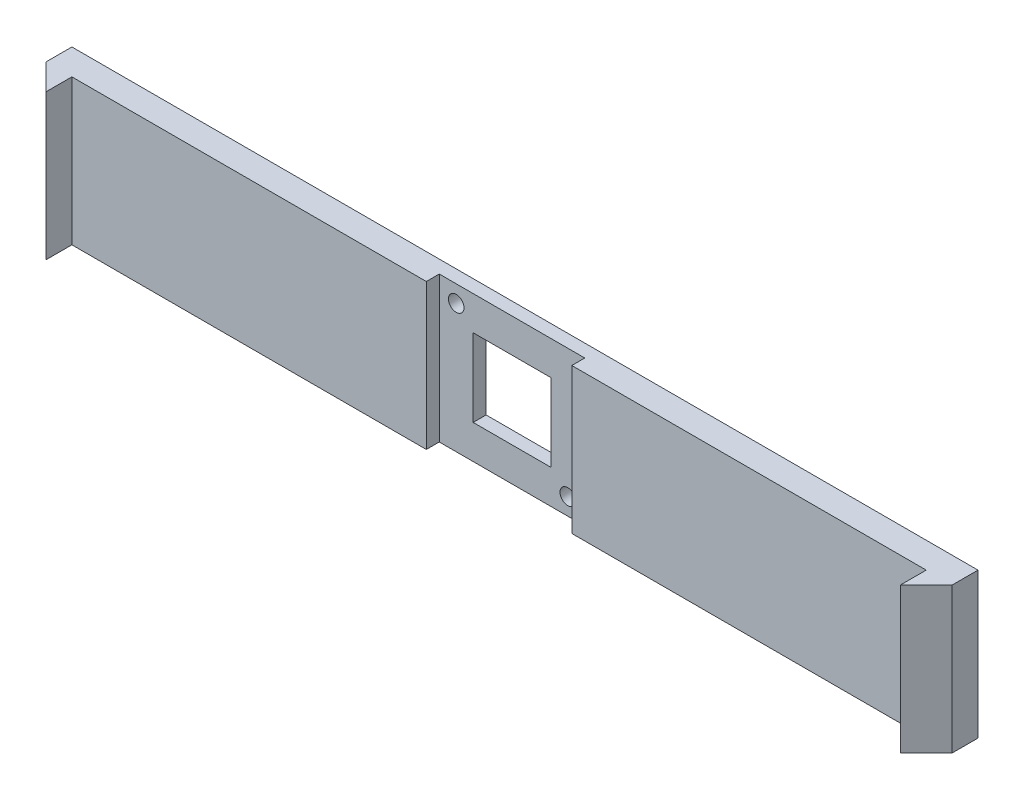
SolidWorks part; units mm, degrees
ref_plane "Front Plane" through (0, 0, 0) normal (0, 0, 1) x (1, 0, 0)
ref_plane "Top Plane" through (0, 0, 0) normal (0, 1, 0) x (1, 0, 0)
ref_plane "Right Plane" through (0, 0, 0) normal (1, 0, 0) x (0, 0, -1)
sketch "Sketch1" plane through (0, 0, 0) normal (0, 0, 1) x (1, 0, 0)
  line L1 (-165, -28.1) -> (165, -28.1)
  line L2 (-165, -28.1) -> (-165, 28.1)
  line L3 (-165, 28.1) -> (165, 28.1)
  line L4 (165, -28.1) -> (165, 28.1)
  line L5 (-165, -28.1) -> (165, 28.1) construction
  line L6 (-165, 28.1) -> (165, -28.1) construction
  point P0 (0, 0)
extrude "Boss-Extrude1" add sketch "Sketch1" along normal blind 10
sketch "Sketch2" plane through (0, 0, 10) normal (0, 0, 1) x (1, 0, 0)
  line L2 (165, 28.1) -> (-165, 28.1) construction
  line L3 (-28.1, -28.1) -> (28.1, -28.1)
  line L4 (-28.1, -28.1) -> (-28.1, 28.1)
  line L5 (-28.1, 28.1) -> (28.1, 28.1)
  line L6 (28.1, -28.1) -> (28.1, 28.1)
  point P8 (0, 0)
extrude "Cut-Extrude1" cut sketch "Sketch2" against normal blind 5
sketch "Sketch3" plane through (165, 0, 0) normal (1, 0, 0) x (0, 0, -1)
  line L1 (-10, 28.1) -> (0, 28.1)
  line L2 (-10, 28.1) -> (-10, -28.1)
  line L3 (-10, -28.1) -> (0, -28.1)
  line L4 (0, 28.1) -> (0, -28.1)
extrude "Boss-Extrude2" add sketch "Sketch3" along normal blind 10
sketch "Sketch4" plane through (0, 0, 10) normal (0, 0, 1) x (1, 0, 0)
  line L0 (28.1, -28.1) -> (175, -28.1) construction
  line L1 (175, 28.1) -> (165, 28.1)
  line L2 (175, 28.1) -> (175, -28.1)
  line L3 (175, -28.1) -> (165, -28.1)
  line L4 (165, 28.1) -> (165, -28.1)
extrude "Boss-Extrude3" add sketch "Sketch4" along normal blind 10
sketch "Sketch5" plane through (0, 28.1, 0) normal (0, 1, 0) x (1, 0, 0)
  line L0 (165, -20) -> (175, -10)
  line L1 (175, 0) -> (175, -20) construction
  line L2 (175, -10) -> (175, -20)
  line L3 (175, -20) -> (165, -20)
extrude "Cut-Extrude2" cut sketch "Sketch5" against normal blind 56.2
sketch "Sketch6" plane through (-165, 0, 0) normal (-1, 0, 0) x (0, 0, 1)
  line L1 (0, -28.1) -> (10, -28.1)
  line L2 (0, -28.1) -> (0, 28.1)
  line L3 (0, 28.1) -> (10, 28.1)
  line L4 (10, -28.1) -> (10, 28.1)
extrude "Boss-Extrude4" add sketch "Sketch6" along normal blind 10
sketch "Sketch7" plane through (0, 0, 10) normal (0, 0, 1) x (1, 0, 0)
  line L0 (-28.1, 28.1) -> (-175, 28.1) construction
  line L1 (-175, -28.1) -> (-165, -28.1)
  line L2 (-175, -28.1) -> (-175, 28.1)
  line L3 (-175, 28.1) -> (-165, 28.1)
  line L4 (-165, -28.1) -> (-165, 28.1)
extrude "Boss-Extrude5" add sketch "Sketch7" along normal blind 10
sketch "Sketch8" plane through (0, 28.1, 0) normal (0, 1, 0) x (1, 0, 0)
  line L0 (-165, -20) -> (-175, -10)
  line L1 (-175, -20) -> (-175, 0) construction
  line L2 (-175, -10) -> (-175, -20)
  line L3 (-175, -20) -> (-165, -20)
extrude "Cut-Extrude3" cut sketch "Sketch8" against normal blind 56.2
sketch "Sketch9" plane through (0, 0, 5) normal (0, 0, 1) x (1, 0, 0)
  line L3 (-15, -15) -> (15, -15)
  line L4 (-15, -15) -> (-15, 15)
  line L5 (-15, 15) -> (15, 15)
  line L6 (15, -15) -> (15, 15)
  point P4 (0, 0)
extrude "Cut-Extrude4" cut sketch "Sketch9" against normal blind 5
sketch "Sketch10" plane through (0, 0, 5) normal (0, 0, 1) x (1, 0, 0)
  circle A0 centre (-21.55, 21.55) radius 3
  circle A1 centre (21.55, -21.55) radius 3
extrude "Cut-Extrude5" cut sketch "Sketch10" against normal blind 5
